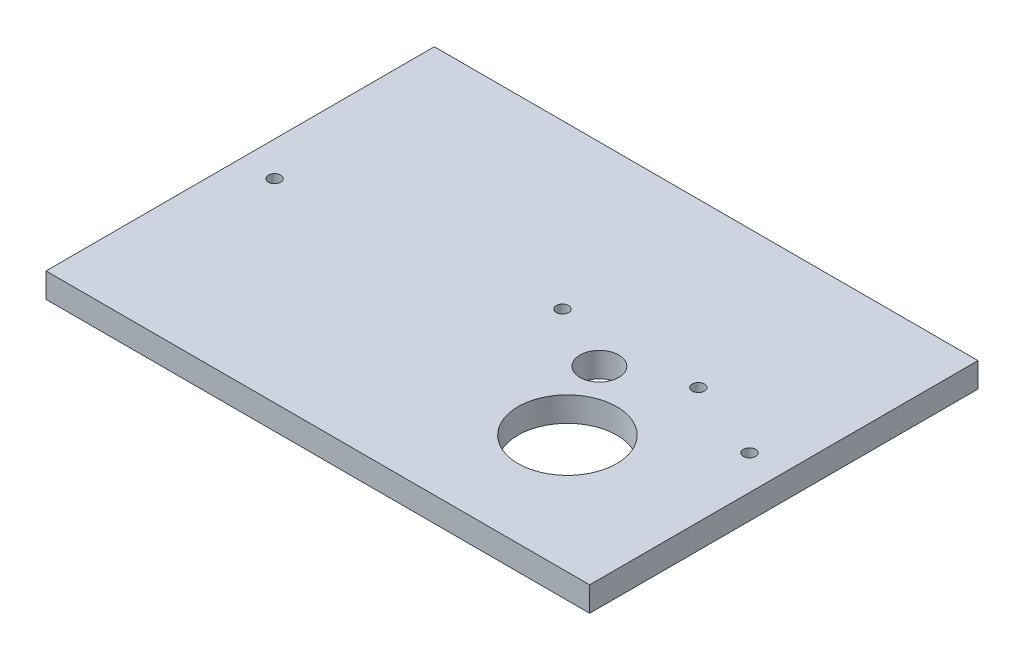
SolidWorks part; units mm, degrees
material "Oak"
ref_plane "Front Plane" through (0, 0, 0) normal (0, 0, 1) x (1, 0, 0)
ref_plane "Top Plane" through (0, 0, 0) normal (0, 1, 0) x (1, 0, 0)
ref_plane "Right Plane" through (0, 0, 0) normal (1, 0, 0) x (0, 0, -1)
sketch "Sketch1" plane through (0, 0, 0) normal (0, 1, 0) x (1, 0, 0)
  line L1 (0, 0) -> (140, 0)
  line L2 (0, 0) -> (0, 100)
  line L3 (0, 100) -> (140, 100)
  line L4 (140, 0) -> (140, 100)
  dimension "D1" = 140
  dimension "D2" = 100
extrude "Boss-Extrude1" add sketch "Sketch1" along normal blind 6.35
sketch "Sketch2" plane through (0, 6.35, 0) normal (0, 1, 0) x (1, 0, 0)
  line L0 (0, 50) -> (140, 50) construction
  line L1 (0, 100) -> (0, 0) construction
  line L2 (140, 0) -> (140, 100) construction
  line L3 (70, 100) -> (70, 0) construction
  line L4 (140, 100) -> (0, 100) construction
  line L5 (0, 0) -> (140, 0) construction
  line L6 (92.5, 50) -> (114.578, 11.7597) construction
  circle A0 centre (103.75, 30.5144) radius 12.705
  circle A1 centre (92.5, 50) radius 5
  point P12 (92.5, 50)
  point P13 (70, 50)
  dimension "D3" = 25.41
  dimension "D5" = 10
  dimension "D1" = 22.5
  dimension "D2" = 120
  dimension "D4" = 22.5
  dimension "D6" = 30.5144
  dimension "D7" = 36.25
extrude "Cut-Extrude1" cut sketch "Sketch2" against normal blind 10
sketch "Sketch3" plane through (0, 6.35, 0) normal (0, 1, 0) x (1, 0, 0)
  line L0 (0, 100) -> (0, 0) construction
  line L1 (140, 0) -> (140, 100) construction
  line L2 (140, 100) -> (0, 100) construction
  circle A0 centre (8.85, 50) radius 1.5875
  circle A1 centre (131.15, 50) radius 1.5875
  circle A2 centre (75, 58) radius 1.5875
  circle A3 centre (110, 58) radius 1.5875
  circle A4 centre (92.5, 50) radius 5 construction
  dimension "D1" = 3.175
  dimension "D2" = 3.175
  dimension "D3" = 3.175
  dimension "D4" = 3.175
  dimension "D9" = 17.5
  dimension "D10" = 8
  dimension "D11" = 17.5
  dimension "D12" = 8
  dimension "D5" = 8.85
  dimension "D6" = 8.85
  dimension "D7" = 50
  dimension "D8" = 50
extrude "Cut-Extrude2" cut sketch "Sketch3" against normal blind 10
